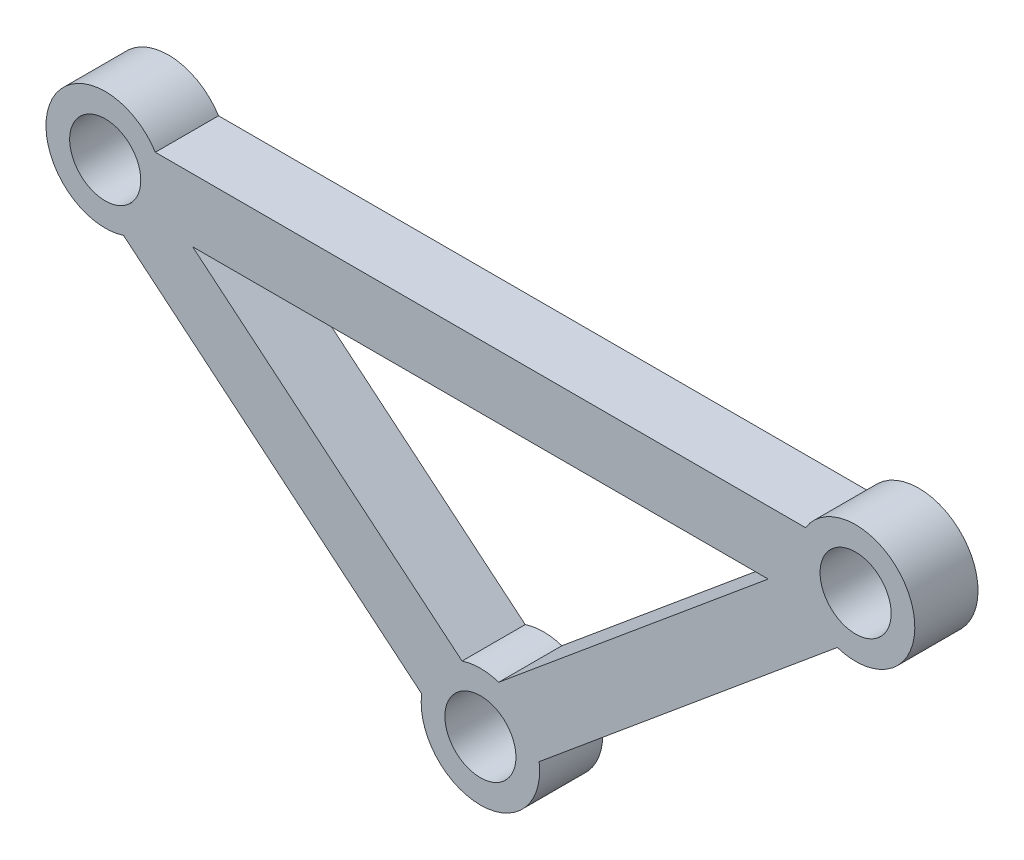
SolidWorks part; units mm, degrees
ref_plane "Front Plane" through (0, 0, 0) normal (0, 0, 1) x (1, 0, 0)
ref_plane "Top Plane" through (0, 0, 0) normal (0, 1, 0) x (1, 0, 0)
ref_plane "Right Plane" through (0, 0, 0) normal (1, 0, 0) x (0, 0, -1)
sketch "Sketch1" plane through (0, 0, 0) normal (0, 0, 1) x (1, 0, 0)
  line L4 (0, -16.2396) -> (0, 23.2604) construction
  line L5 (47.5, 23.2604) -> (-47.5, 23.2604) construction
  line L6 (-47.5, 23.2604) -> (0, -16.2396) construction
  line L7 (0, -16.2396) -> (47.5, 23.2604) construction
  line L8 (-50.0576, 20.1849) -> (-44.9424, 26.336) construction
  line L9 (-2.434, -19.4137) -> (2.434, -13.0654) construction
  line L10 (-47.5, 27.2604) -> (-47.5, 19.2604) construction
  line L11 (44.9424, 26.336) -> (50.0576, 20.1849) construction
  line L12 (47.5, 27.2604) -> (47.5, 19.2604) construction
  line L13 (-2.5576, -13.164) -> (2.5576, -19.3151) construction
  line L14 (45.1795, 16.1284) -> (7.4356, -15.2586)
  line L17 (36.4339, 19.2604) -> (2.3205, -9.1076)
  line L18 (41.1557, 27.2604) -> (-41.1557, 27.2604)
  line L19 (0, -11.0372) -> (-0.0023, -11.0391)
  line L20 (-45.1792, 16.1286) -> (-7.4351, -15.2554)
  line L21 (-36.4348, 19.2604) -> (36.4339, 19.2604)
  line L22 (-2.3236, -9.1086) -> (-36.4348, 19.2604)
  line L23 (0, -11.0411) -> (-0.0023, -11.0391)
  circle A0 centre (-47.5, 23.2604) radius 4.5
  circle A2 centre (47.5, 23.2604) radius 4.5
  circle A3 centre (0, -16.2396) radius 4.5
  arc A4 (-40.0645, 22.2791) -> (-40, 23.2604) centre (-47.5, 23.2604) ccw
  arc A5 (45.1795, 16.1284) -> (41.1557, 27.2604) centre (47.5, 23.2604) ccw
  arc A6 (2.3205, -9.1076) -> (-2.3236, -9.1086) centre (0, -16.2396) ccw
  circle A7 centre (-47.5, 23.2604) radius 7.5 construction
  arc A8 (-41.1557, 27.2604) -> (-45.1792, 16.1286) centre (-47.5, 23.2604) ccw
  circle A9 centre (47.5, 23.2604) radius 7.5 construction
  circle A10 centre (0, -16.2396) radius 7.5 construction
  arc A11 (-7.4351, -15.2554) -> (7.4356, -15.2586) centre (0, -16.2396) ccw
  point P10 (0, 23.2604)
  point P18 (-23.75, 3.5104)
  point P19 (-47.5, 23.2604)
  point P20 (-47.5, 23.2604)
  point P23 (0, -16.2396)
  point P25 (-47.5, 23.2604)
  point P29 (47.5, 23.2604)
  point P30 (47.5, 23.2604)
  point P33 (47.5, 23.2604)
  point P36 (0, -16.2396)
  dimension "D1" = 9
  dimension "D2" = 9
  dimension "D3" = 9
  dimension "D4" = 39.5
  dimension "D5" = 95
  dimension "D9" = 8
  dimension "D10" = 8
  dimension "D11" = 8
  dimension "D12" = 8
  dimension "D13" = 8
  dimension "D14" = 8
  dimension "D6" = 3
  dimension "D7" = 3
  dimension "D8" = 3
extrude "Boss-Extrude1" add sketch "Sketch1" along normal blind 8
